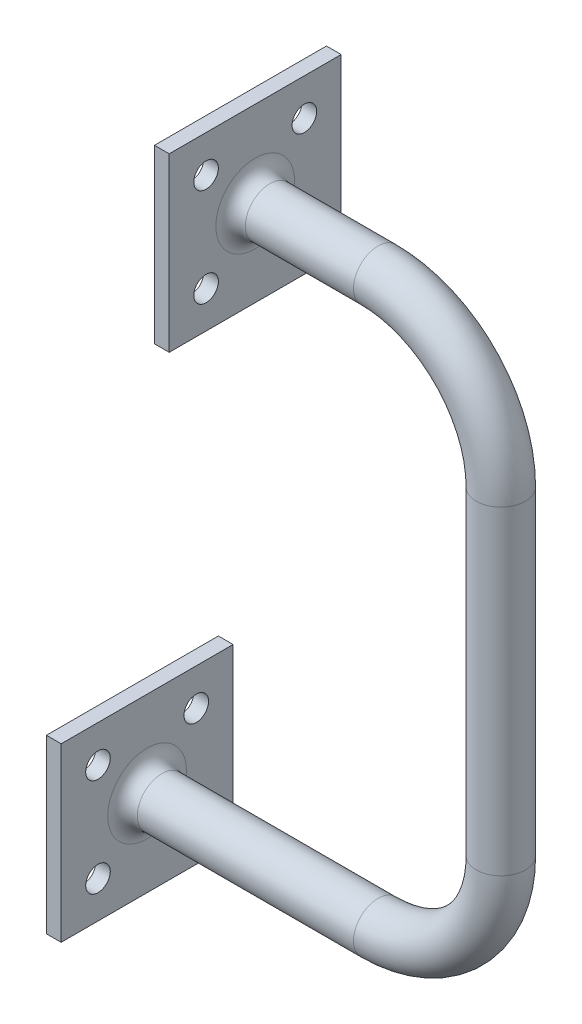
SolidWorks part; units mm, degrees
ref_plane "Front Plane" through (0, 0, 0) normal (0, 0, 1) x (1, 0, 0)
ref_plane "Top Plane" through (0, 0, 0) normal (0, 1, 0) x (1, 0, 0)
ref_plane "Right Plane" through (0, 0, 0) normal (1, 0, 0) x (0, 0, -1)
sketch "Sketch1" plane through (0, 0, 0) normal (1, 0, 0) x (0, 0, -1)
  line L1 (-17.5, -17.5) -> (17.5, -17.5)
  line L2 (-17.5, -17.5) -> (-17.5, 17.5)
  line L3 (-17.5, 17.5) -> (17.5, 17.5)
  line L4 (17.5, -17.5) -> (17.5, 17.5)
  line L5 (-17.5, -17.5) -> (17.5, 17.5) construction
  line L6 (-17.5, 17.5) -> (17.5, -17.5) construction
  point P0 (0, 0)
extrude "Boss-Extrude1" add sketch "Sketch1" along normal blind 3
sketch "Sketch2" plane through (3, 0, 0) normal (1, 0, 0) x (0, 0, -1)
  circle A0 centre (10, 10) radius 2.5
extrude "Cut-Extrude1" cut sketch "Sketch2" against normal through all
pattern_linear "LPattern1" count 2 spacing 20 along (0, 0, 1) count 2 spacing 20 along (0, -1, 0) of "Cut-Extrude1"
sketch "Sketch5" plane through (3, 0, 0) normal (1, 0, 0) x (0, 0, -1)
  line L0 (0, 6.2733) -> (0, 17.5) construction
sketch "Sketch6" plane through (0, 17.5, 0) normal (0, 1, 0) x (1, 0, 0)
  line L0 (0, 0) -> (10.5171, 0) construction
ref_plane "Plane1" through (0, 0, 0) normal (0, 0, 1) x (1, 0, 0)
sketch "Sketch8" plane through (0, 0, 0) normal (0, 0, 1) x (1, 0, 0)
  line L0 (0, 0) -> (50, 0)
  line L1 (75, 25) -> (75, 90)
  line L2 (50, 115) -> (25, 115)
  arc A0 (50, 0) -> (75, 25) centre (50, 25) ccw
  arc A1 (50, 115) -> (75, 90) centre (50, 90) cw
sketch "Sketch9" plane through (3, 0, 0) normal (1, 0, 0) x (0, 0, -1)
  circle A0 centre (0, 0) radius 5
sweep "Sweep1" add profiles "Sketch9" path "Sketch8"
sketch "Sketch10" plane through (25, 0, 0) normal (-1, 0, 0) x (0, 0, 1)
  line L1 (-17.5, 97.5) -> (17.5, 97.5)
  line L2 (-17.5, 97.5) -> (-17.5, 132.5)
  line L3 (-17.5, 132.5) -> (17.5, 132.5)
  line L4 (17.5, 97.5) -> (17.5, 132.5)
  line L5 (-17.5, 97.5) -> (17.5, 132.5) construction
  line L6 (-17.5, 132.5) -> (17.5, 97.5) construction
  point P0 (0, 115)
extrude "Boss-Extrude2" add sketch "Sketch10" along normal blind 3
sketch "Sketch11" plane through (22, 0, 0) normal (-1, 0, 0) x (0, 0, 1)
  line L0 (-17.5, 132.5) -> (17.5, 97.5) construction
  line L1 (-17.5, 97.5) -> (17.5, 132.5) construction
  circle A0 centre (9.999, 124.999) radius 2.5
extrude "Cut-Extrude2" cut sketch "Sketch11" against normal through all
pattern_linear "LPattern4" count 2 spacing 20 along (0, 0, -1) count 2 spacing 20 along (0, -1, 0) of "Cut-Extrude2"
fillet "Fillet1" radius 3 1 edges at (25, 115, -5)
fillet "Fillet2" radius 3 1 edges at (3, 0, -5)
